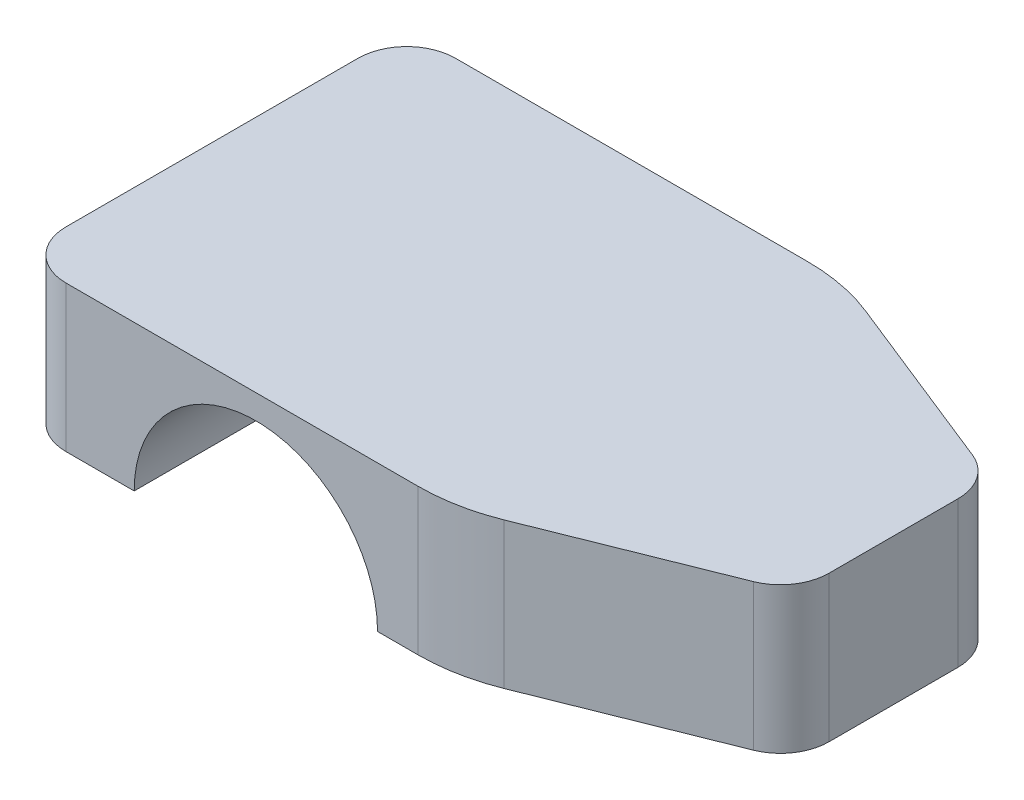
SolidWorks part; units mm, degrees
ref_plane "Front Plane" through (0, 0, 0) normal (0, 0, 1) x (1, 0, 0)
ref_plane "Top Plane" through (0, 0, 0) normal (0, 1, 0) x (1, 0, 0)
ref_plane "Right Plane" through (0, 0, 0) normal (1, 0, 0) x (0, 0, -1)
sketch "Sketch1" plane through (0, 0, 0) normal (0, 1, 0) x (1, 0, 0)
  line L0 (-10, 20) -> (15, 10)
  line L1 (-55, 20) -> (-10, 20)
  line L2 (-55, 20) -> (-55, -20)
  line L3 (-55, -20) -> (-10, -20)
  line L4 (-10, 20) -> (-10, -20) construction
  line L5 (-55, 20) -> (-10, -20) construction
  line L6 (-55, -20) -> (-10, 20) construction
  line L7 (15, 10) -> (15, -10)
  line L8 (15, -10) -> (-10, -20)
  point P0 (-32.5, 0)
  point P8 (15, 0)
  dimension "D1" = 15
  dimension "D2" = 70
  dimension "D3" = 40
  dimension "D4" = 20
  dimension "D5" = 45
extrude "Boss-Extrude1" add sketch "Sketch1" along normal blind 15
sketch "Sketch2" plane through (0, 0, 0) normal (0, 0, 1) x (1, 0, 0)
  line L0 (-55, 0) -> (-10, 0) construction
  line L1 (-55, 15) -> (-55, 0) construction
  circle A0 centre (-30.5, 0) radius 12.5
  dimension "D1" = 25
  dimension "D2" = 12
extrude "Cut-Extrude1" cut sketch "Sketch2" against normal through all both and the other way through all
fillet "Fillet2" radius 5 4 edges at (-55, 7.5, 20) (15, 7.5, -10) (15, 7.5, 10) (-55, 7.5, -20)
fillet "Fillet3" radius 20 2 edges at (-10, 7.5, -20) (-10, 7.5, 20)
